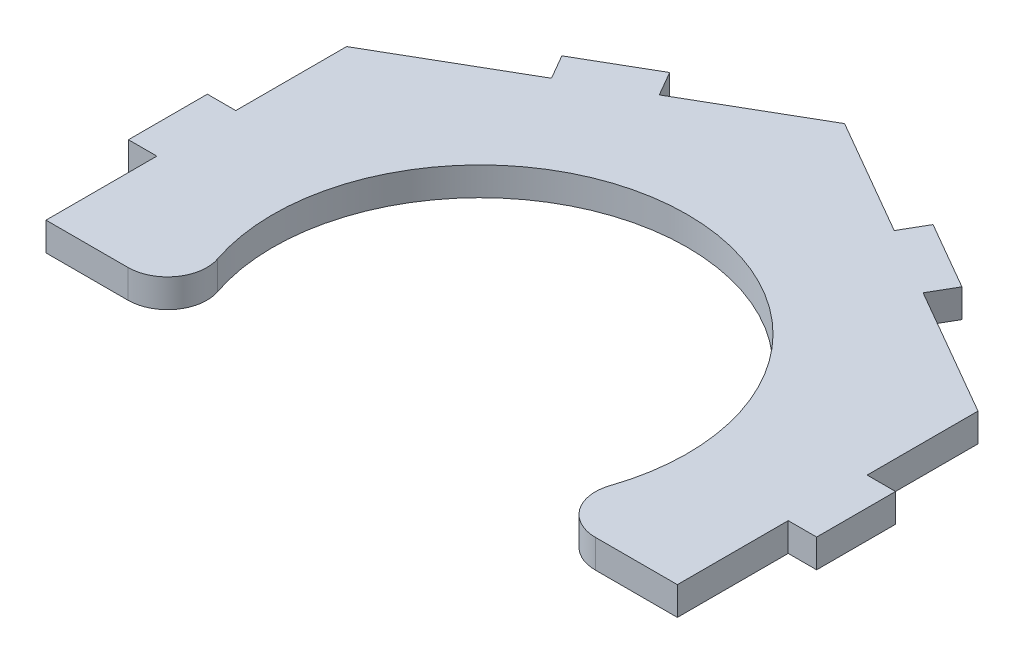
SolidWorks part; units mm, degrees
ref_plane "Front Plane" through (0, 0, 0) normal (0, 0, 1) x (1, 0, 0)
ref_plane "Top Plane" through (0, 0, 0) normal (0, 1, 0) x (1, 0, 0)
ref_plane "Right Plane" through (0, 0, 0) normal (1, 0, 0) x (0, 0, -1)
sketch "Sketch1" plane through (0, 0, 0) normal (0, 1, 0) x (1, 0, 0)
  line L0 (-50.8, -19.05) -> (-37.6006, -19.05)
  line L1 (50.8, -19.05) -> (50.8, 29.3294)
  line L2 (50.8, 29.3294) -> (0, 58.6588)
  line L3 (0, 58.6588) -> (-50.8, 29.3294)
  line L4 (-50.8, 29.3294) -> (-50.8, -19.05)
  line L7 (-25.4, -43.9941) -> (-9.8224, -52.9878) [skipped]
  line L8 (25.4, -43.9941) -> (40.9776, -35.0003) [skipped]
  line L9 (50.8, -19.05) -> (37.6006, -19.05)
  arc A0 (50.8, 0) -> (-50.8, 0) centre (0, 0) ccw construction
  arc A1 (31.5845, -10.668) -> (-31.5845, -10.668) centre (0, 0) ccw
  arc A2 (37.6006, -19.05) -> (31.5845, -10.668) centre (37.6006, -12.7) cw
  arc A3 (-37.6006, -19.05) -> (-31.5845, -10.668) centre (-37.6006, -12.7) ccw
  point P8 (-36.1544, 20.8738)
  dimension "D1" = 33.3375
  dimension "D2" = 50.8
  dimension "D4" = 6.35
  dimension "D3" = 19.05
extrude "Boss-Extrude1" add sketch "Sketch1" along normal blind 4.572
sketch "Sketch2" plane through (0, 4.572, 0) normal (0, 1, 0) x (1, 0, 0)
  line L0 (-50.8, 11.4897) -> (-55.372, 11.4897)
  line L1 (-50.8, 29.3294) -> (-50.8, -19.05) construction
  line L2 (-55.372, 11.4897) -> (-55.372, -1.2103)
  line L3 (-55.372, -1.2103) -> (-50.8, -1.2103)
  line L4 (-29.9028, 41.3944) -> (-32.1888, 45.3539)
  line L5 (0, 58.6588) -> (-50.8, 29.3294) construction
  line L6 (-32.1888, 45.3539) -> (-21.1903, 51.7039)
  line L7 (-21.1903, 51.7039) -> (-18.9043, 47.7444)
  line L8 (18.9043, 47.7444) -> (21.1903, 51.7039)
  line L9 (50.8, 29.3294) -> (0, 58.6588) construction
  line L10 (21.1903, 51.7039) -> (32.1888, 45.3539)
  line L11 (32.1888, 45.3539) -> (29.9028, 41.3944)
  line L13 (50.8, 11.4897) -> (55.372, 11.4897)
  line L14 (50.8, -19.05) -> (50.8, 29.3294) construction
  line L15 (55.372, 11.4897) -> (55.372, -1.2103)
  line L16 (55.372, -1.2103) -> (50.8, -1.2103)
  line L20 (-50.8, -1.2103) -> (-50.8, 11.4897)
  line L21 (-29.9028, 41.3944) -> (-18.9043, 47.7444)
  line L22 (18.9043, 47.7444) -> (29.9028, 41.3944)
  line L23 (50.8, 11.4897) -> (50.8, -1.2103)
  point P24 (-50.8, 5.1397)
  point P25 (-55.372, 5.1397)
  point P26 (55.372, 5.1397)
  dimension "D1" = 24.13
  dimension "D2" = 24.13
  dimension "D3" = 12.7
  dimension "D4" = 4.572
extrude "Boss-Extrude2" add sketch "Sketch2" against normal blind 4.572
